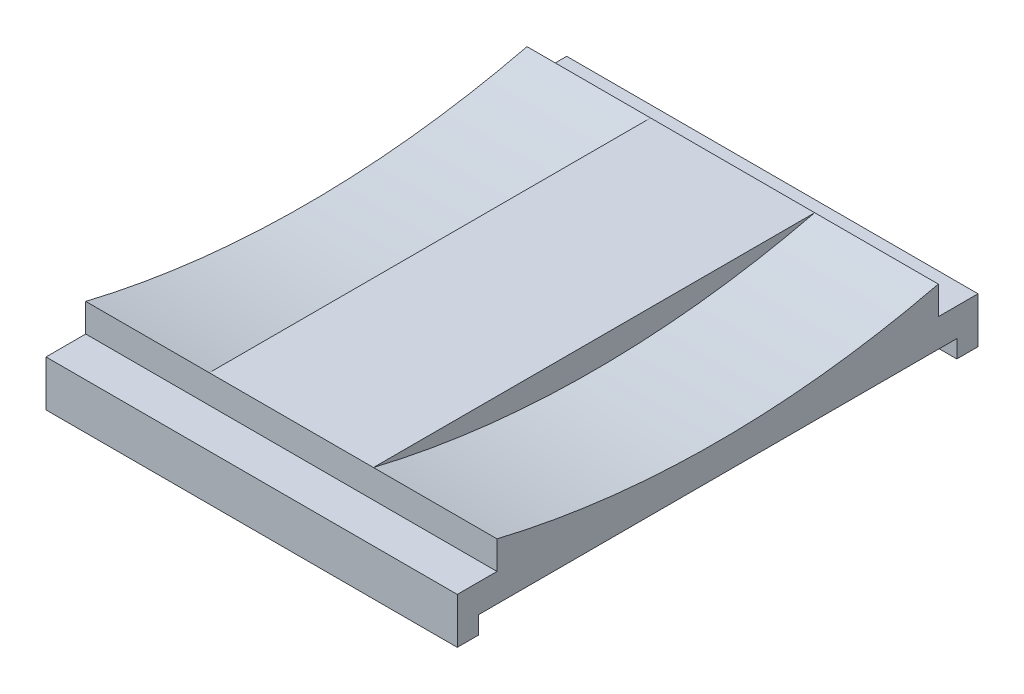
SolidWorks part; units mm, degrees
ref_plane "Front Plane" through (0, 0, 0) normal (0, 0, 1) x (1, 0, 0)
ref_plane "Top Plane" through (0, 0, 0) normal (0, 1, 0) x (1, 0, 0)
ref_plane "Right Plane" through (0, 0, 0) normal (1, 0, 0) x (0, 0, -1)
sketch "Sketch1" plane through (0, 0, 0) normal (1, 0, 0) x (0, 0, -1)
  line L0 (-43.6251, -15.6973) -> (-16.5251, -15.6973)
  line L2 (-44.8251, -14.0973) -> (-44.8251, -16.6973)
  line L3 (-44.8251, -16.6973) -> (-15.3251, -16.6973)
  line L4 (-15.3251, -14.0973) -> (-15.3251, -16.6973)
  line L5 (-16.5251, -15.6973) -> (-16.5251, -16.6973)
  line L6 (-43.6251, -15.6973) -> (-43.6251, -16.6973)
  line L7 (-42.5751, -14.0973) -> (-44.8251, -14.0973)
  line L8 (-42.5751, -14.0973) -> (-17.5751, -14.0973)
  line L9 (-42.5751, -14.0973) -> (-42.5751, -12.4973)
  line L10 (-42.5751, -12.4973) -> (-17.5751, -12.4973)
  line L11 (-17.5751, -14.0973) -> (-17.5751, -12.4973)
  line L12 (-17.5751, -14.0973) -> (-15.3251, -14.0973)
  arc A0 (-42.5751, -12.4973) -> (-17.5751, -12.4973) centre (-30.0751, 39.2581) ccw
  point P13 (0, 0)
  dimension "D6" = 29.5
  dimension "D1" = 1.2
  dimension "D2" = 1.2
  dimension "D4" = 2.6
  dimension "D5" = 1.6
  dimension "D7" = 25
extrude "Boss-Extrude1" add sketch "Sketch1" along normal blind 23.3
sketch "Sketch2" plane through (0, 0, 42.5751) normal (0, 0, 1) x (1, 0, 0)
  line L0 (23.3, -12.4973) -> (0, -12.4973) construction
  line L1 (7, -12.4973) -> (16.3, -12.4973)
  line L2 (7, -12.4973) -> (7, -14.0973)
  line L3 (7, -14.0973) -> (16.3, -14.0973)
  line L4 (16.3, -12.4973) -> (16.3, -14.0973)
  line L5 (23.3, -14.0973) -> (0, -14.0973) construction
  line L6 (0, -14.0973) -> (0, -12.4973) construction
  line L7 (23.3, -14.0973) -> (23.3, -12.4973) construction
  dimension "D1" = 7
  dimension "D2" = 7
extrude "Boss-Extrude2" add sketch "Sketch2" against normal up to body separate body
sketch "Sketch3" plane through (0, -15.6973, 0) normal (0, -1, 0) x (1, 0, 0)
  line L6 (23.3, 43.6251) -> (23.3, 16.5251) construction
  line L7 (0, 43.6251) -> (23.3, 43.6251)
  line L8 (0, 43.6251) -> (0, 41.6251)
  line L9 (0, 41.6251) -> (23.3, 41.6251)
  line L10 (23.3, 43.6251) -> (23.3, 41.6251)
  line L11 (0, 30.0751) -> (23.3, 30.0751) construction
  line L12 (0, 43.6251) -> (0, 16.5251) construction
  line L13 (11.65, 44.8251) -> (11.65, 15.3251) construction
  line L14 (23.3, 43.6251) -> (21.3, 43.6251)
  line L15 (23.3, 43.6251) -> (23.3, 30.0751)
  line L16 (23.3, 30.0751) -> (21.3, 30.0751)
  line L17 (21.3, 43.6251) -> (21.3, 30.0751)
  line L18 (23.3, 44.8251) -> (0, 44.8251) construction
  line L19 (23.3, 15.3251) -> (0, 15.3251) construction
  line L20 (9, 38.4251) -> (2, 38.4251)
  line L21 (14.3, 41.6251) -> (21.3, 41.6251)
  line L22 (14.3, 41.6251) -> (14.3, 38.4251)
  line L23 (14.3, 38.4251) -> (21.3, 38.4251)
  line L24 (21.3, 41.6251) -> (21.3, 38.4251)
  line L25 (2, 41.6251) -> (2, 38.4251)
  line L26 (9, 41.6251) -> (2, 41.6251)
  line L27 (9, 41.6251) -> (9, 38.4251)
  line L28 (14.3, 21.7251) -> (21.3, 21.7251)
  line L29 (21.3, 18.5251) -> (21.3, 21.7251)
  line L30 (14.3, 18.5251) -> (21.3, 18.5251)
  line L31 (14.3, 18.5251) -> (14.3, 21.7251)
  line L32 (9, 18.5251) -> (9, 21.7251)
  line L33 (9, 18.5251) -> (2, 18.5251)
  line L34 (2, 18.5251) -> (2, 21.7251)
  line L35 (9, 21.7251) -> (2, 21.7251)
  line L36 (9, 18.5251) -> (14.3, 18.5251)
  line L38 (9, 41.6251) -> (14.3, 41.6251)
  line L39 (9, 41.6251) -> (9, 18.5251)
  line L40 (9, 18.5251) -> (14.3, 18.5251)
  line L41 (14.3, 41.6251) -> (14.3, 18.5251)
  circle A0 centre (21.3, 41.6251) radius 2
  circle A1 centre (2, 41.6251) radius 2
  circle A2 centre (21.3, 18.5251) radius 2
  circle A3 centre (2, 18.5251) radius 2
  point P27 (21.3, 41.6251)
  dimension "D3" = 3.2
  dimension "D1" = 2
  dimension "D2" = 2
extrude "Cut-Extrude2" cut sketch "Sketch3" against normal blind 1.6 contours L26 A1 L25 L20 L27 | L41 L22 L9 L27 L39 L32 L36 L31 | A0 L9 L22 L23 L24 | L30 A2 L29 L28 L31 | A3 L33 L32 L35 L34
sketch "Sketch7" plane through (14.3, 0, 0) normal (-1, 0, 0) x (0, 0, 1)
  line L0 (21.7251, -14.0973) -> (21.7251, -15.6973) construction
  arc A0 (21.7251, -14.0973) -> (38.4251, -14.0973) centre (30.0751, 25.0215) ccw
